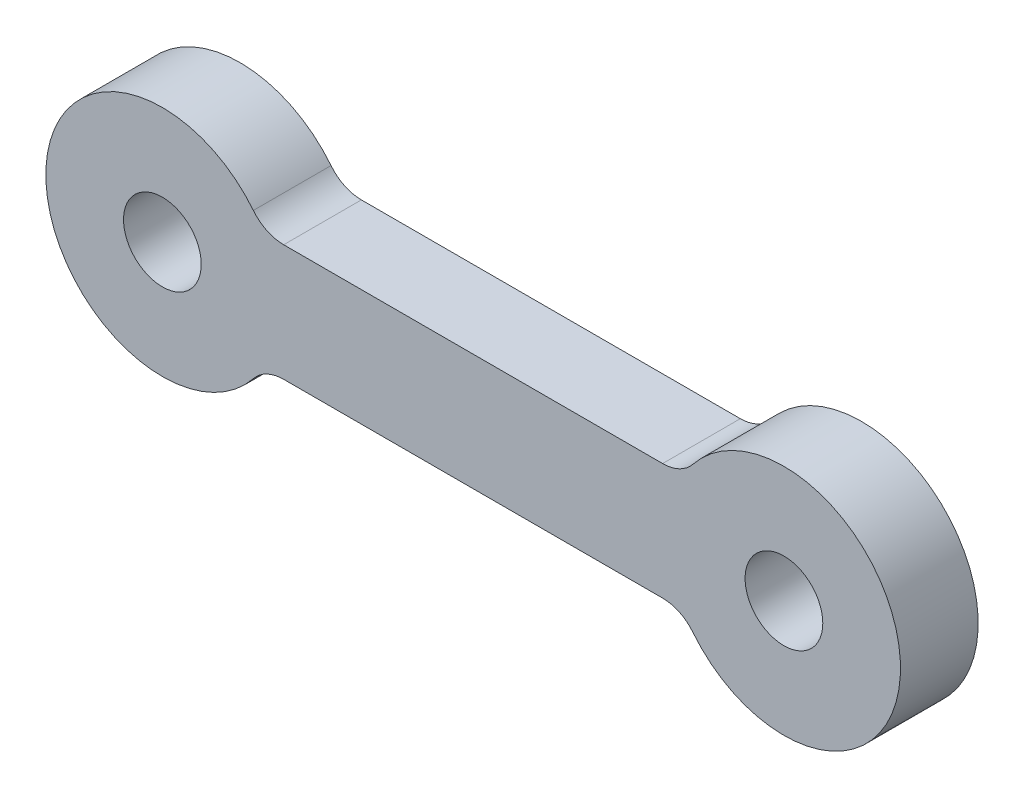
SolidWorks part; units mm, degrees
ref_plane "Front" through (0, 0, 0) normal (0, 0, 1) x (1, 0, 0)
ref_plane "Top" through (0, 0, 0) normal (0, 1, 0) x (1, 0, 0)
ref_plane "Right" through (0, 0, 0) normal (1, 0, 0) x (0, 0, -1)
sketch "Sketch1" plane through (0, 0, 0) normal (0, 0, 1) x (1, 0, 0)
  line L0 (-82.55, 0) -> (-19.05, 0) construction
  line L1 (-85.1022, -9.525) -> (-16.4978, -9.525)
  line L2 (-85.1022, 9.525) -> (-16.4978, 9.525)
  line L3 (-82.55, 9.525) -> (-19.05, 9.525) construction
  line L4 (-82.55, -9.525) -> (-19.05, -9.525) construction
  circle A0 centre (0, 0) radius 6.35
  arc A1 (-16.4978, -9.525) -> (-16.4978, 9.525) centre (0, 0) ccw
  circle A2 centre (-101.6, 0) radius 6.35
  arc A3 (-85.1022, 9.525) -> (-85.1022, -9.525) centre (-101.6, 0) ccw
  arc A4 (-82.55, 0) -> (-85.1022, 9.525) centre (-101.6, 0) ccw construction
  arc A5 (-85.1022, -9.525) -> (-82.55, 0) centre (-101.6, 0) ccw construction
  arc A6 (-19.05, 0) -> (-16.4978, -9.525) centre (0, 0) ccw construction
  arc A7 (-16.4978, 9.525) -> (-19.05, 0) centre (0, 0) ccw construction
  dimension "D1" = 12.7
  dimension "D3" = 38.1
  dimension "D2" = 101.6
  dimension "D4" = 9.525
  dimension "D5" = 9.525
extrude "Boss-Extrude1" add sketch "Sketch1" along normal blind 12.7
fillet "Fillet1" radius 6.35 4 edges at (-16.4978, -9.525, 6.35) (-85.1022, -9.525, 6.35) (-16.4978, 9.525, 6.35) (-85.1022, 9.525, 6.35)
